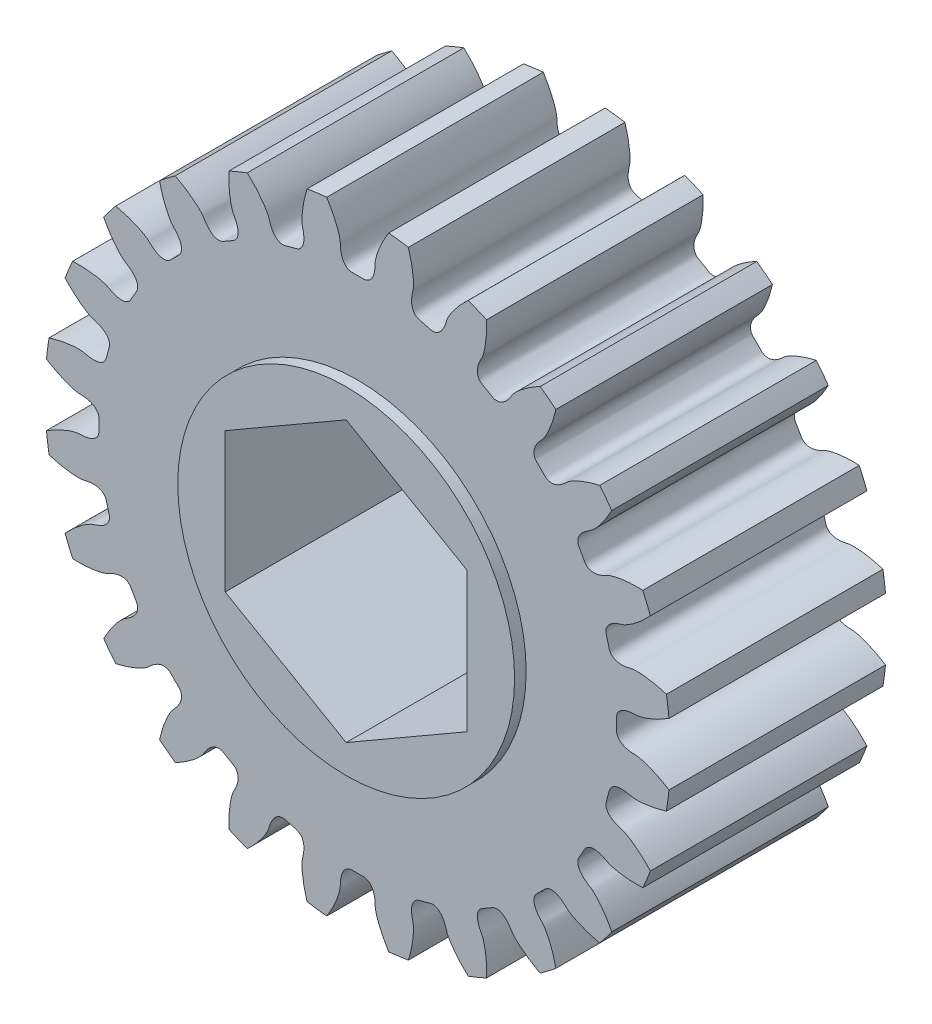
SolidWorks part; units mm, degrees
ref_plane "Front Plane" through (0, 0, 0) normal (0, 0, 1) x (1, 0, 0)
ref_plane "Top Plane" through (0, 0, 0) normal (0, 1, 0) x (1, 0, 0)
ref_plane "Right Plane" through (0, 0, 0) normal (1, 0, 0) x (0, 0, -1)
ref_plane "Plane4" through (0, 0, -5.715) normal (0, 0, -1) x (-1, 0, 0)
sketch "Sketch1" plane through (0, 0, -5.715) normal (0, 0, -1) x (-1, 0, 0)
  arc A0 (-12.7729, 10.461) -> (-13.4104, 9.6302) centre (0, 0) ccw
  arc A1 (-15.0452, 6.7987) -> (-15.446, 5.8312) centre (0, 0) ccw
  arc A2 (-16.2922, 2.673) -> (-16.4289, 1.6348) centre (0, 0) ccw
  arc A3 (-16.4289, -1.6348) -> (-16.2922, -2.673) centre (0, 0) ccw
  arc A4 (-15.446, -5.8312) -> (-15.0452, -6.7987) centre (0, 0) ccw
  arc A5 (-13.4104, -9.6302) -> (-12.7729, -10.461) centre (0, 0) ccw
  arc A6 (-10.461, -12.7729) -> (-9.6302, -13.4104) centre (0, 0) ccw
  arc A7 (-6.7987, -15.0452) -> (-5.8312, -15.446) centre (0, 0) ccw
  arc A8 (-2.673, -16.2922) -> (-1.6348, -16.4289) centre (0, 0) ccw
  arc A9 (1.6348, -16.4289) -> (2.673, -16.2922) centre (0, 0) ccw
  arc A10 (5.8312, -15.446) -> (6.7987, -15.0452) centre (0, 0) ccw
  arc A11 (9.6302, -13.4104) -> (10.461, -12.7729) centre (0, 0) ccw
  arc A12 (12.7729, -10.461) -> (13.4104, -9.6302) centre (0, 0) ccw
  arc A13 (15.0452, -6.7987) -> (15.446, -5.8312) centre (0, 0) ccw
  arc A14 (16.2922, -2.673) -> (16.4289, -1.6348) centre (0, 0) ccw
  arc A15 (16.4289, 1.6348) -> (16.2922, 2.673) centre (0, 0) ccw
  arc A16 (15.446, 5.8312) -> (15.0452, 6.7987) centre (0, 0) ccw
  arc A17 (13.4104, 9.6302) -> (12.7729, 10.461) centre (0, 0) ccw
  arc A18 (10.461, 12.7729) -> (9.6302, 13.4104) centre (0, 0) ccw
  arc A19 (6.7987, 15.0452) -> (5.8312, 15.446) centre (0, 0) ccw
  arc A20 (2.673, 16.2922) -> (1.6348, 16.4289) centre (0, 0) ccw
  arc A21 (-1.6348, 16.4289) -> (-2.673, 16.2922) centre (0, 0) ccw
  arc A22 (-5.8312, 15.446) -> (-6.7987, 15.0452) centre (0, 0) ccw
  arc A23 (-9.6302, 13.4104) -> (-10.461, 12.7729) centre (0, 0) ccw
  spline S0 degree 3 number of poles 101 (-15.0452, 6.7987) -> (-13.4104, 9.6302)
  spline S1 degree 3 number of poles 101 (-16.2922, 2.673) -> (-15.446, 5.8312)
  spline S2 degree 3 number of poles 101 (-16.4289, -1.6348) -> (-16.4289, 1.6348)
  spline S3 degree 3 number of poles 101 (-15.446, -5.8312) -> (-16.2922, -2.673)
  spline S4 degree 3 number of poles 101 (-13.4104, -9.6302) -> (-15.0452, -6.7987)
  spline S5 degree 3 number of poles 101 (-10.461, -12.7729) -> (-12.7729, -10.461)
  spline S6 degree 3 number of poles 101 (-6.7987, -15.0452) -> (-9.6302, -13.4104)
  spline S7 degree 3 number of poles 101 (-2.673, -16.2922) -> (-5.8312, -15.446)
  spline S8 degree 3 number of poles 101 (1.6348, -16.4289) -> (-1.6348, -16.4289)
  spline S9 degree 3 number of poles 101 (5.8312, -15.446) -> (2.673, -16.2922)
  spline S10 degree 3 number of poles 101 (9.6302, -13.4104) -> (6.7987, -15.0452)
  spline S11 degree 3 number of poles 101 (12.7729, -10.461) -> (10.461, -12.7729)
  spline S12 degree 3 number of poles 101 (15.0452, -6.7987) -> (13.4104, -9.6302)
  spline S13 degree 3 number of poles 101 (16.2922, -2.673) -> (15.446, -5.8312)
  spline S14 degree 3 number of poles 101 (16.4289, 1.6348) -> (16.4289, -1.6348)
  spline S15 degree 3 number of poles 101 (15.446, 5.8312) -> (16.2922, 2.673)
  spline S16 degree 3 number of poles 101 (13.4104, 9.6302) -> (15.0452, 6.7987)
  spline S17 degree 3 number of poles 101 (10.461, 12.7729) -> (12.7729, 10.461)
  spline S18 degree 3 number of poles 101 (6.7987, 15.0452) -> (9.6302, 13.4104)
  spline S19 degree 3 number of poles 101 (2.673, 16.2922) -> (5.8312, 15.446)
  spline S20 degree 3 number of poles 101 (-1.6348, 16.4289) -> (1.6348, 16.4289)
  spline S21 degree 3 number of poles 101 (-5.8312, 15.446) -> (-2.673, 16.2922)
  spline S22 degree 3 number of poles 101 (-9.6302, 13.4104) -> (-6.7987, 15.0452)
  spline S23 degree 3 number of poles 101 (-12.7729, 10.461) -> (-10.461, 12.7729)
extrude "Boss-Extrude1" add sketch "Sketch1" against normal blind 11.43
sketch "Sketch2" plane through (0, 0, -5.715) normal (0, 0, -1) x (-1, 0, 0)
  circle A0 centre (0, 0) radius 8.89
extrude "Boss-Extrude2" add sketch "Sketch2" along normal blind 0.6096
sketch "Sketch3" plane through (0, 0, 5.715) normal (0, 0, 1) x (1, 0, 0)
  circle A0 centre (0, 0) radius 8.89
extrude "Boss-Extrude3" add sketch "Sketch3" along normal blind 0.6096
sketch "Sketch4" plane through (0, 0, 6.3246) normal (0, 0, 1) x (1, 0, 0)
  line L0 (6.3881, -3.6882) -> (6.3881, 3.6882)
  line L1 (6.3881, 3.6882) -> (0, 7.3763)
  line L2 (0, 7.3763) -> (-6.3881, 3.6882)
  line L3 (-6.3881, 3.6882) -> (-6.3881, -3.6882)
  line L4 (-6.3881, -3.6882) -> (0, -7.3763)
  line L5 (0, -7.3763) -> (6.3881, -3.6882)
extrude "Cut-Extrude1" cut sketch "Sketch4" against normal through all
